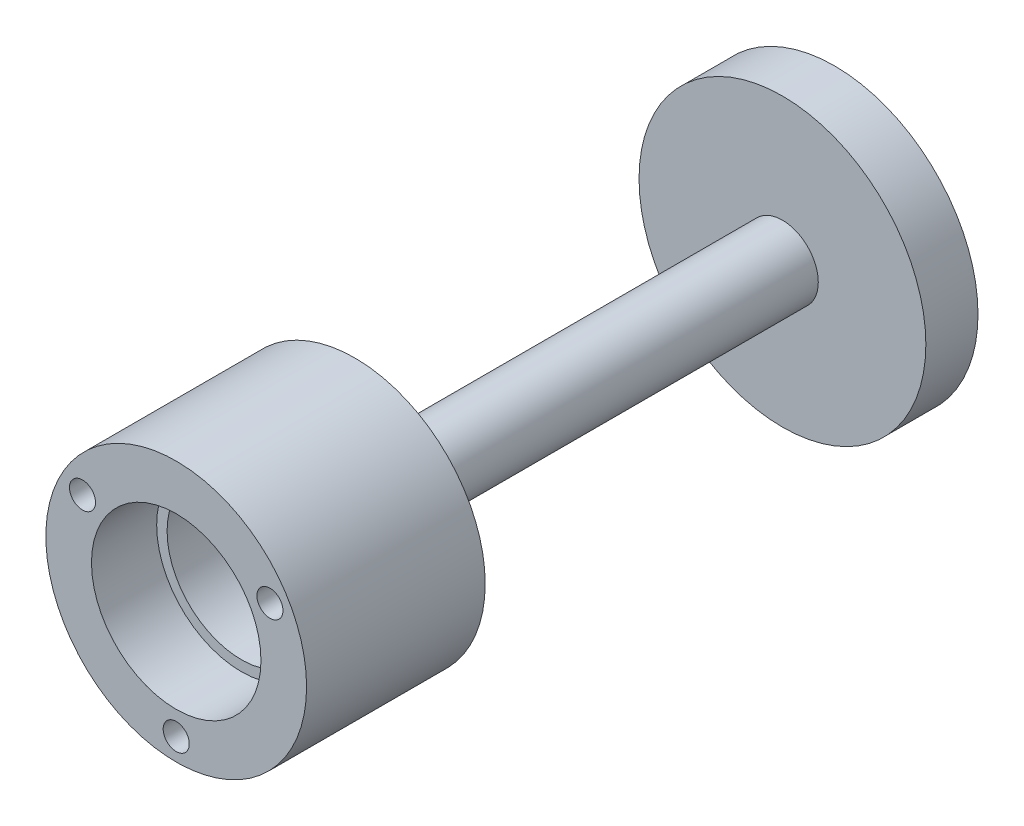
SolidWorks part; units mm, degrees
material "AISI 4340 Steel, normalized"
ref_plane "Front Plane" through (0, 0, 0) normal (0, 0, 1) x (1, 0, 0)
ref_plane "Top Plane" through (0, 0, 0) normal (0, 1, 0) x (1, 0, 0)
ref_plane "Right Plane" through (0, 0, 0) normal (1, 0, 0) x (0, 0, -1)
sketch "Sketch1" plane through (0, 0, 0) normal (0, 0, 1) x (1, 0, 0)
  circle A0 centre (0, 0) radius 11
extrude "Mounting_Flange" add sketch "Sketch1" along normal blind 4 from offset 4
sketch "Sketch2" plane through (0, 0, 0) normal (0, 0, 1) x (1, 0, 0)
  circle A0 centre (0, 0) radius 2.75
extrude "D5p5_Central_Post" add sketch "Sketch2" along normal blind 32.81
sketch "Sketch3" plane through (0, 0, 0) normal (0, 0, 1) x (1, 0, 0)
  circle A0 centre (0, 0) radius 10
extrude "Closed_Floor_Below_Shaft_Nose" add sketch "Sketch3" along normal blind 2.2 from offset 32.8
sketch "Sketch4" plane through (0, 0, 0) normal (0, 0, 1) x (1, 0, 0)
  circle A0 centre (0, 0) radius 10
  circle A1 centre (0, 0) radius 5.7
extrude "Shaft_And_Clip_Clearance" add sketch "Sketch4" along normal blind 6.5 from offset 35
sketch "Sketch5" plane through (0, 0, 0) normal (0, 0, 1) x (1, 0, 0)
  circle A0 centre (0, 0) radius 10
  circle A1 centre (0, 0) radius 6.5
extrude "Lower_686ZZ_Seat" add sketch "Sketch5" along normal blind 5 from offset 41.5
sketch "Sketch6" plane through (0, 0, -4) normal (0, 0, -1) x (-1, 0, 0)
  circle A0 centre (-7.188, 4.15) radius 1
  circle A1 centre (7.188, 4.15) radius 1
  circle A2 centre (0, -8.3) radius 1
extrude "Base_Three_M2_Blind_Thread_Major_Envelopes" cut sketch "Sketch6" against normal blind 3.6
sketch "Sketch7" plane through (0, 0, 46.5) normal (0, 0, 1) x (1, 0, 0)
  circle A0 centre (7.188, 4.15) radius 1
  circle A1 centre (-7.188, 4.15) radius 1
  circle A2 centre (0, -8.3) radius 1
extrude "Top_Cap_Three_M2_Blind_Thread_Major_Envelopes" cut sketch "Sketch7" against normal blind 4.3
